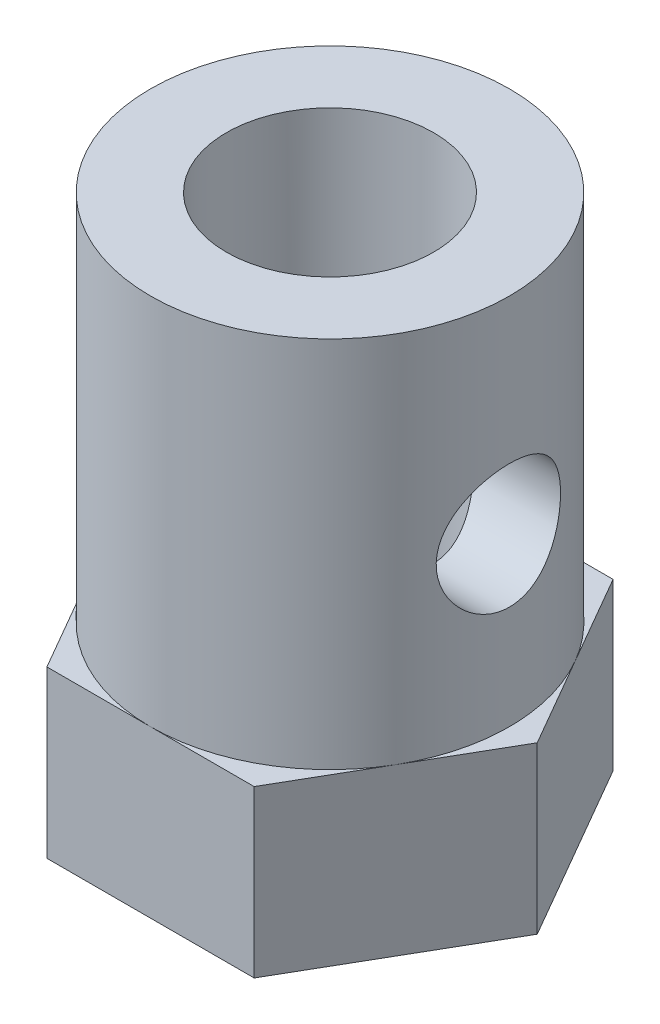
SolidWorks part; units mm, degrees
material "5052-H34"
ref_plane "前视基准面" through (0, 0, 0) normal (0, 0, 1) x (1, 0, 0)
ref_plane "上视基准面" through (0, 0, 0) normal (0, 1, 0) x (1, 0, 0)
ref_plane "右视基准面" through (0, 0, 0) normal (1, 0, 0) x (0, 0, -1)
sketch "草图2" plane through (0, 0, 0) normal (0, 1, 0) x (1, 0, 0)
  line L0 (0, 0) -> (5, 0)
  line L1 (0, 0) -> (2.5, 4.3301)
  line L2 (0, 0) -> (-2.5, 4.3301)
  line L3 (0, 0) -> (-5, 0)
  line L4 (0, 0) -> (-2.5, -4.3301)
  line L5 (0, 0) -> (2.5, -4.3301)
  line L6 (5, 0) -> (2.5, 4.3301)
  line L7 (2.5, 4.3301) -> (-2.5, 4.3301)
  line L8 (-2.5, 4.3301) -> (-5, 0)
  line L9 (-2.5, -4.3301) -> (2.5, -4.3301)
  line L10 (2.5, -4.3301) -> (5, 0)
  line L11 (-2.5, -4.3301) -> (-5, 0)
extrude "凸台-拉伸1" add sketch "草图2" along normal blind 4 contours L2 L8 L3 | L11 L4 L3 | L4 L9 L5 | L5 L10 L0 | L0 L6 L1 | L1 L7 L2
sketch "草图3" plane through (0, 4, 0) normal (0, 1, 0) x (1, 0, 0)
  circle A0 centre (0, 0) radius 2.5
  circle A1 centre (0, 0) radius 4.3301
extrude "凸台-拉伸2" add sketch "草图3" along normal blind 9
sketch "草图4" plane through (0, 0, 0) normal (0, -1, 0) x (1, 0, 0)
  circle A0 centre (0, 0) radius 1.5
extrude "切除-拉伸1" cut sketch "草图4" against normal blind 15
sketch "草图5" plane through (0, 0, 0) normal (1, 0, 0) x (0, 0, -1)
  circle A0 centre (0, 8) radius 1.5
extrude "切除-拉伸2" cut sketch "草图5" against normal through all both and the other way through all
